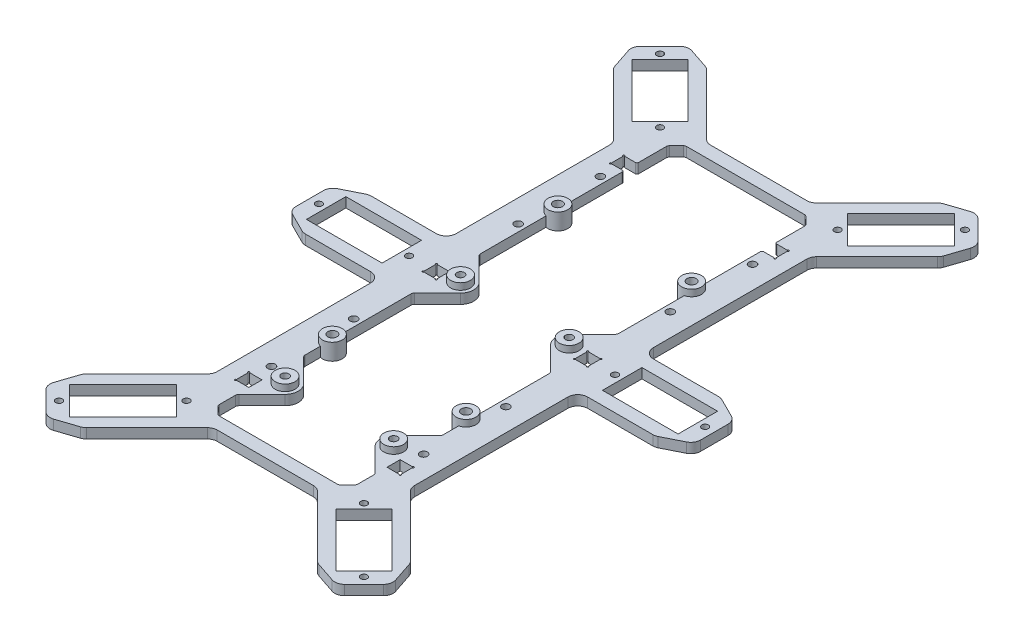
SolidWorks part; units mm, degrees
ref_plane "前视基准面" through (0, 0, 0) normal (0, 0, 1) x (1, 0, 0)
ref_plane "上视基准面" through (0, 0, 0) normal (0, 1, 0) x (1, 0, 0)
ref_plane "右视基准面" through (0, 0, 0) normal (1, 0, 0) x (0, 0, -1)
sketch "草图1" plane through (0, 0, 0) normal (0, 1, 0) x (1, 0, 0)
  line L0 (-30, 65) -> (-20, 75)
  line L1 (-20.5, 38) -> (20.5, 38) construction
  line L2 (-20.5, 38) -> (-20.5, -38) construction
  line L3 (-20.5, -38) -> (20.5, -38) construction
  line L4 (20.5, 38) -> (20.5, -38) construction
  line L5 (-20.5, 38) -> (20.5, -38) construction
  line L6 (-20.5, -38) -> (20.5, 38) construction
  line L7 (-20, 75) -> (20, 75)
  line L8 (-30, 65) -> (-30, -65)
  line L9 (-20, -75) -> (20, -75)
  line L10 (30, 65) -> (30, -65)
  line L11 (-30, 75) -> (30, -75) construction
  line L12 (-30, -75) -> (30, 75) construction
  line L13 (20, 75) -> (30, 65)
  line L14 (30, -65) -> (20, -75)
  line L15 (-30, -65) -> (-20, -75)
  line L16 (-1.6778, 71) -> (18.3431, 71)
  line L17 (18.3431, 71) -> (21, 68.3431)
  line L18 (21, 68.3431) -> (21, -68.3431)
  line L19 (0, 0) -> (21, 0) construction
  line L20 (0, 0) -> (0, 17.6719) construction
  line L21 (18.3431, -71) -> (21, -68.3431)
  line L22 (-1.6778, -71) -> (18.3431, -71)
  line L23 (1.6778, -71) -> (-18.3431, -71)
  line L24 (-18.3431, -71) -> (-21, -68.3431)
  line L25 (-21, 68.3431) -> (-21, -68.3431)
  line L26 (-18.3431, 71) -> (-21, 68.3431)
  line L27 (1.6778, 71) -> (-18.3431, 71)
  point P0 (0, 0)
  point P6 (0, 0)
  dimension "D1" = 41
  dimension "D2" = 76
  dimension "D3" = 60
  dimension "D4" = 150
  dimension "D5" = 9
  dimension "D6" = 4
  dimension "D11" = 4
extrude "凸台-拉伸1" add sketch "草图1" along normal mid plane 3 contours L8 L15 L9 L14 L10 L13 L7 L0 L27 L16 L17 L18 L21 L22 L23 L24 L25 L26
sketch "草图2" plane through (0, 1.5, 0) normal (0, 1, 0) x (1, 0, 0)
  line L0 (0, 0) -> (45, 0) construction
  line L1 (33.5, 6) -> (56.5, 6)
  line L2 (33.5, 6) -> (33.5, -6)
  line L3 (33.5, -6) -> (56.5, -6)
  line L4 (56.5, 6) -> (56.5, -6)
  line L5 (33.5, 6) -> (56.5, -6) construction
  line L6 (33.5, -6) -> (56.5, 6) construction
  line L7 (25, 70) -> (46.3546, 91.3546) construction
  line L8 (28.5, 10) -> (60.5, 10)
  line L9 (28.5, 10) -> (28.5, -10)
  line L10 (28.5, -10) -> (60.5, -10)
  line L11 (61.5, 9) -> (61.5, -9)
  line L12 (28.5, 10) -> (61.5, -10) construction
  line L13 (28.5, -10) -> (61.5, 10) construction
  line L14 (20, 75) -> (30, 65) construction
  line L15 (24.2929, 77.7782) -> (32.7782, 69.2929)
  line L20 (24.2929, 77.7782) -> (40.5563, 94.0416)
  line L21 (32.7782, 69.2929) -> (49.0416, 85.5563)
  line L22 (40.5563, 94.0416) -> (49.0416, 85.5563)
  line L23 (44.799, 89.799) -> (28.5355, 73.5355) construction
  line L33 (54.6985, 85.5563) -> (30, 60.8579)
  line L34 (40.5563, 99.6985) -> (15.8579, 75)
  line L35 (41.9706, 99.6985) -> (54.6985, 86.9706)
  line L36 (20, 75) -> (30, 65)
  line L37 (45, 0) -> (58.7, 0) construction
  line L38 (45, 0) -> (45, 5.0576) construction
  line L39 (32.4246, 85.9099) -> (40.9099, 77.4246) construction
  line L40 (30, 65) -> (30, 60.8579)
  line L42 (20, 75) -> (15.8579, 75)
  arc A0 (60.5, -10) -> (61.5, -9) centre (60.5, -9) ccw
  arc A1 (60.5, 10) -> (61.5, 9) centre (60.5, 9) cw
  circle A4 centre (58.7, 0) radius 1
  circle A5 centre (31.3, 0) radius 1
  circle A6 centre (46.3546, 91.3546) radius 1
  circle A7 centre (26.9799, 71.9799) radius 1
  arc A8 (54.6985, 85.5563) -> (54.6985, 86.9706) centre (53.9914, 86.2635) ccw
  arc A9 (40.5563, 99.6985) -> (41.9706, 99.6985) centre (41.2635, 98.9914) cw
  point P0 (45, 0)
  dimension "D9" = 1
  dimension "D10" = 2
  dimension "D12" = 2
  dimension "D17" = 1
  dimension "D1" = 23
  dimension "D2" = 12
  dimension "D3" = 20
  dimension "D4" = 5
  dimension "D5" = 45
  dimension "D6" = 23
  dimension "D7" = 12
  dimension "D8" = 4
  dimension "D11" = 27.4
  dimension "D13" = 27.4
  dimension "D14" = 5
  dimension "D15" = 4
  dimension "D16" = 5
extrude "凸台-拉伸2" add sketch "草图2" against normal through all
mirror "镜向1" about plane through (0, 0, 0) normal (0, 0, 1) of "凸台-拉伸2"
mirror "镜向2" about plane through (0, 0, 0) normal (1, 0, 0) of "镜向1", "凸台-拉伸2"
sketch "草图3" plane through (0, 1.5, 0) normal (0, 1, 0) x (1, 0, 0)
  line L0 (16.51, 0.8674) -> (21, 0.8674) construction
  line L1 (21, 68.3431) -> (21, -68.3431) construction
  line L2 (21, 11.0142) -> (13.6816, 3.6958)
  line L3 (21, 2.25) -> (21, 54.75) construction
  line L4 (21, -9.2794) -> (13.6816, -1.961)
  line L5 (21, 11.0142) -> (21, -9.2794)
  line L6 (21, -54.75) -> (21, -2.25) construction
  line L9 (5.744, -25.8034) -> (19.0373, -25.8034) construction
  line L10 (19.0373, 0.8674) -> (19.0373, -52.4742) construction
  line L11 (21, -62.621) -> (21, -42.3273)
  line L12 (21, -42.3273) -> (13.6816, -49.6457)
  line L13 (21, -62.621) -> (13.6816, -55.3026)
  line L14 (0, -63) -> (0, -56.7778) construction
  line L15 (-4.17, -63) -> (4.17, -63) construction
  line L16 (-21, 11.0142) -> (-21, -9.2794)
  line L17 (-21, -9.2794) -> (-13.6816, -1.961)
  line L18 (-21, 11.0142) -> (-13.6816, 3.6958)
  line L19 (-21, -62.621) -> (-13.6816, -55.3026)
  line L20 (-21, -62.621) -> (-21, -42.3273)
  line L21 (-21, -42.3273) -> (-13.6816, -49.6457)
  circle A0 centre (16.51, 0.8674) radius 1.15
  circle A1 centre (16.51, -52.4727) radius 1.15
  circle A2 centre (-16.51, -52.4727) radius 1.15
  circle A3 centre (-16.51, 0.8674) radius 1.15
  arc A4 (13.6816, 3.6958) -> (13.6816, -1.961) centre (16.51, 0.8674) ccw
  arc A6 (13.6816, -55.3026) -> (13.6816, -49.6457) centre (16.51, -52.4742) cw
  arc A7 (-13.6816, 3.6958) -> (-13.6816, -1.961) centre (-16.51, 0.8674) cw
  arc A8 (-13.6816, -55.3026) -> (-13.6816, -49.6457) centre (-16.51, -52.4742) ccw
  dimension "D1" = 2.3
  dimension "D2" = 2.3
  dimension "D3" = 2.3
  dimension "D4" = 2.3
  dimension "D5" = 8
  dimension "D6" = 45
extrude "凸台-拉伸3" add sketch "草图3" against normal blind 3
sketch "草图4" plane through (0, 1.5, 0) normal (0, 1, 0) x (1, 0, 0)
  line L0 (0, -71) -> (0, -45.2799) construction
  line L1 (-18.3431, -71) -> (18.3431, -71) construction
  circle A0 centre (16.51, -52.4727) radius 1.15 construction
  circle A1 centre (16.51, 0.8674) radius 1.15 construction
  circle A2 centre (16.51, -52.4727) radius 1.15
  circle A3 centre (16.51, 0.8674) radius 1.15
  circle A4 centre (16.51, -52.4727) radius 3
  circle A5 centre (16.51, 0.8674) radius 3
  circle A6 centre (-16.51, 0.8674) radius 3
  circle A7 centre (-16.51, 0.8674) radius 1.15
  circle A8 centre (-16.51, -52.4727) radius 3
  circle A9 centre (-16.51, -52.4727) radius 1.15
  dimension "D1" = 6
  dimension "D2" = 6
extrude "凸台-拉伸4" add sketch "草图4" along normal blind 2
sketch "草图5" plane through (0, 1.5, 0) normal (0, 1, 0) x (1, 0, 0)
  line L0 (21, 68.3431) -> (21, 11.0142) construction
  line L1 (21, 2) -> (25, 2)
  line L2 (21, 2) -> (21, -2)
  line L3 (21, -2) -> (25, -2)
  line L4 (25, 2) -> (25, -2)
  line L5 (21, 2) -> (25, -2) construction
  line L6 (21, -2) -> (25, 2) construction
  line L7 (0, 0) -> (23, 0) construction
  line L8 (21, -55) -> (25, -55)
  line L9 (21, 59) -> (25, 59)
  line L10 (21, 59) -> (21, 55)
  line L11 (21, 55) -> (25, 55)
  line L12 (25, 59) -> (25, 55)
  line L13 (21, 59) -> (25, 55) construction
  line L14 (21, 55) -> (25, 59) construction
  line L15 (25, -59) -> (25, -55)
  line L16 (21, -59) -> (25, -59)
  line L17 (21, -59) -> (21, -55)
  line L18 (0, 0) -> (0, 27.4251) construction
  line L19 (-21, -59) -> (-21, -55)
  line L20 (-21, -59) -> (-25, -59)
  line L21 (-25, -59) -> (-25, -55)
  line L22 (-21, -55) -> (-25, -55)
  line L23 (-21, -2) -> (-25, -2)
  line L24 (-25, 2) -> (-25, -2)
  line L25 (-21, 2) -> (-25, 2)
  line L26 (-21, 2) -> (-21, -2)
  line L27 (-21, 55) -> (-25, 55)
  line L28 (-25, 59) -> (-25, 55)
  line L29 (-21, 59) -> (-25, 59)
  line L30 (-21, 59) -> (-21, 55)
  point P0 (23, 0)
  point P10 (23, 57)
  dimension "D1" = 4
  dimension "D2" = 4
  dimension "D3" = 4
  dimension "D4" = 4
  dimension "D5" = 110
extrude "切除-拉伸1" cut sketch "草图5" against normal blind 3
sketch "草图6" plane through (0, 1.5, 0) normal (0, 1, 0) x (1, 0, 0)
  line L0 (0, 0) -> (5.4753, 0) construction
  line L1 (0, 0) -> (0, 5.5062) construction
  circle A0 centre (25, 59) radius 0.25
  circle A1 centre (25, 55) radius 0.25
  circle A2 centre (25, 2) radius 0.25
  circle A3 centre (21, 2) radius 0.25
  circle A4 centre (25, -55) radius 0.25
  circle A5 centre (25, -59) radius 0.25
  circle A6 centre (21, -2) radius 0.25
  circle A7 centre (25, -2) radius 0.25
  circle A8 centre (-25, -2) radius 0.25
  circle A9 centre (-21, -2) radius 0.25
  circle A10 centre (-25, -59) radius 0.25
  circle A11 centre (-25, -55) radius 0.25
  circle A12 centre (-21, 2) radius 0.25
  circle A13 centre (-25, 2) radius 0.25
  circle A14 centre (-25, 55) radius 0.25
  circle A15 centre (-25, 59) radius 0.25
  dimension "D1" = 0.5
  dimension "D2" = 0.5
  dimension "D3" = 0.5
  dimension "D4" = 0.5
extrude "切除-拉伸2" cut sketch "草图6" against normal blind 3
fillet "圆角1" radius 0.5 4 edges at (-21, 0, -55) (-21, 0, -59) (21, 0, -59) (21, 0, -55)
fillet "圆角2" radius 1 16 edges at (-18.3431, 0, -71) (-21, 0, -68.3431) (18.3431, 0, -71) (21, 0, -68.3431) (21, 0, -11.0142) (-21, 0, -11.0142) (-21, 0, 9.2794) (21, 0, 9.2794) (21, 0, 42.3273) (-21, 0, 42.3273) (-21, 0, 62.621) (-21, 0, 68.3431) (-18.3431, 0, 71) (21, 0, 62.621) (21, 0, 68.3431) (18.3431, 0, 71)
fillet "圆角3" radius 3 6 edges at (30, 0, -10) (-30, 0, -10) (-30, 0, -60.8579) (-15.8579, 0, -75) (15.8579, 0, -75) (30, 0, -60.8579)
fillet "圆角4" radius 3 6 edges at (-30, 0, 10) (30, 0, 10) (30, 0, 60.8579) (-30, 0, 60.8579) (-15.8579, 0, 75) (15.8579, 0, 75)
sketch "草图7" plane through (0, 1.5, 0) normal (0, 1, 0) x (1, 0, 0)
  line L0 (23.125, 59) -> (23.125, 50) construction
  line L1 (24.75, 59) -> (21.5, 59) construction
  line L2 (23.125, 50) -> (23.125, 25) construction
  line L3 (0, 0) -> (10.174, 0) construction
  line L4 (0, 0) -> (0, 32.9356) construction
  circle A0 centre (23.125, 50) radius 1.15
  circle A1 centre (23.125, 25) radius 1.15
  circle A2 centre (23.125, -50) radius 1.15
  circle A3 centre (23.125, -25) radius 1.15
  circle A4 centre (-23.125, 50) radius 1.15
  circle A5 centre (-23.125, 25) radius 1.15
  circle A6 centre (-23.125, -25) radius 1.15
  circle A7 centre (-23.125, -50) radius 1.15
  dimension "D1" = 2.3
  dimension "D2" = 2.3
  dimension "D3" = 25
  dimension "D4" = 25
extrude "切除-拉伸3" cut sketch "草图7" against normal through all
sketch "草图8" plane through (0, 1.5, 0) normal (0, 1, 0) x (1, 0, 0)
  line L0 (53.5, 10) -> (61.5, 6)
  line L1 (60.5, 10) -> (33, 10) construction
  line L2 (61.5, -9) -> (61.5, 9) construction
  line L3 (61.5, -9) -> (61.5, -6)
  line L4 (60.5, 10) -> (53.5, 10)
  line L5 (0, 0) -> (10.8263, 0) construction
  line L6 (53.5, -10) -> (61.5, -6)
  line L7 (33, -10) -> (60.5, -10) construction
  line L8 (53.5, -10) -> (60.5, -10)
  line L9 (61.5, 6) -> (61.5, 9)
  line L10 (52.5772, -89.0919) -> (49.7487, -80.6066)
  line L11 (54.6985, -86.9706) -> (41.9706, -99.6985) construction
  line L12 (30.8787, -61.7365) -> (54.6985, -85.5563) construction
  line L13 (26.9799, -71.9799) -> (34.1605, -79.1605) construction
  line L14 (32.7782, -69.2929) -> (49.0416, -85.5563) construction
  line L15 (44.0919, -97.5772) -> (35.6066, -94.7487)
  line L16 (40.5563, -99.6985) -> (16.7365, -75.8787) construction
  line L17 (40.5563, -99.6985) -> (35.6066, -94.7487)
  line L18 (49.7487, -80.6066) -> (54.6985, -85.5563)
  line L19 (54.6985, -86.9706) -> (52.5772, -89.0919)
  line L20 (44.0919, -97.5772) -> (41.9706, -99.6985)
  line L21 (40.5563, 99.6985) -> (35.6066, 94.7487)
  line L22 (44.0919, 97.5772) -> (35.6066, 94.7487)
  line L23 (44.0919, 97.5772) -> (41.9706, 99.6985)
  line L24 (49.7487, 80.6066) -> (54.6985, 85.5563)
  line L25 (52.5772, 89.0919) -> (49.7487, 80.6066)
  line L26 (54.6985, 86.9706) -> (52.5772, 89.0919)
  line L27 (0, 0) -> (0, 12.3518) construction
  line L28 (-54.6985, 86.9706) -> (-52.5772, 89.0919)
  line L29 (-52.5772, 89.0919) -> (-49.7487, 80.6066)
  line L30 (-49.7487, 80.6066) -> (-54.6985, 85.5563)
  line L31 (-44.0919, 97.5772) -> (-41.9706, 99.6985)
  line L32 (-44.0919, 97.5772) -> (-35.6066, 94.7487)
  line L33 (-40.5563, 99.6985) -> (-35.6066, 94.7487)
  line L34 (-44.0919, -97.5772) -> (-41.9706, -99.6985)
  line L35 (-54.6985, -86.9706) -> (-52.5772, -89.0919)
  line L36 (-49.7487, -80.6066) -> (-54.6985, -85.5563)
  line L37 (-40.5563, -99.6985) -> (-35.6066, -94.7487)
  line L38 (-44.0919, -97.5772) -> (-35.6066, -94.7487)
  line L39 (-52.5772, -89.0919) -> (-49.7487, -80.6066)
  line L40 (-61.5, 6) -> (-61.5, 9)
  line L41 (-53.5, -10) -> (-60.5, -10)
  line L42 (-53.5, -10) -> (-61.5, -6)
  line L43 (-60.5, 10) -> (-53.5, 10)
  line L44 (-61.5, -9) -> (-61.5, -6)
  line L45 (-53.5, 10) -> (-61.5, 6)
  arc A0 (61.5, 9) -> (60.5, 10) centre (60.5, 9) ccw construction
  arc A1 (61.5, 9) -> (60.5, 10) centre (60.5, 9) ccw
  arc A2 (60.5, -10) -> (61.5, -9) centre (60.5, -9) ccw construction
  arc A3 (60.5, -10) -> (61.5, -9) centre (60.5, -9) ccw
  arc A4 (40.5563, -99.6985) -> (41.9706, -99.6985) centre (41.2635, -98.9914) ccw construction
  arc A5 (54.6985, -86.9706) -> (54.6985, -85.5563) centre (53.9914, -86.2635) ccw construction
  arc A6 (40.5563, -99.6985) -> (41.9706, -99.6985) centre (41.2635, -98.9914) ccw
  arc A7 (54.6985, -86.9706) -> (54.6985, -85.5563) centre (53.9914, -86.2635) ccw
  arc A8 (40.5563, 99.6985) -> (41.9706, 99.6985) centre (41.2635, 98.9914) cw
  arc A9 (54.6985, 86.9706) -> (54.6985, 85.5563) centre (53.9914, 86.2635) cw
  arc A10 (-54.6985, 86.9706) -> (-54.6985, 85.5563) centre (-53.9914, 86.2635) ccw
  arc A11 (-40.5563, 99.6985) -> (-41.9706, 99.6985) centre (-41.2635, 98.9914) ccw
  arc A12 (-54.6985, -86.9706) -> (-54.6985, -85.5563) centre (-53.9914, -86.2635) cw
  arc A13 (-40.5563, -99.6985) -> (-41.9706, -99.6985) centre (-41.2635, -98.9914) cw
  arc A14 (-60.5, -10) -> (-61.5, -9) centre (-60.5, -9) cw
  arc A15 (-61.5, 9) -> (-60.5, 10) centre (-60.5, 9) cw
  dimension "D1" = 4
  dimension "D2" = 8
  dimension "D3" = 4
  dimension "D4" = 8
extrude "切除-拉伸4" cut sketch "草图8" against normal up to next
fillet "圆角5" radius 3 12 edges at (35.6066, 0, 94.7487) (44.0919, 0, 97.5772) (49.7487, 0, 80.6066) (52.5772, 0, 89.0919) (49.7487, 0, -80.6066) (35.6066, 0, -94.7487) (44.0919, 0, -97.5772) (52.5772, 0, -89.0919) (53.5, 0, -10) (61.5, 0, -6) (53.5, 0, 10) (61.5, 0, 6)
fillet "圆角6" radius 3 12 edges at (-35.6066, 0, -94.7487) (-44.0919, 0, -97.5772) (-52.5772, 0, -89.0919) (-49.7487, 0, -80.6066) (-53.5, 0, 10) (-61.5, 0, 6) (-53.5, 0, -10) (-61.5, 0, -6) (-49.7487, 0, 80.6066) (-52.5772, 0, 89.0919) (-44.0919, 0, 97.5772) (-35.6066, 0, 94.7487)
sketch "草图9" plane through (0, 1.5, 0) normal (0, 1, 0) x (1, 0, 0)
  line L1 (-20.32, 34.29) -> (20.32, 34.29) construction
  line L2 (-20.32, 34.29) -> (-20.32, -34.29) construction
  line L3 (-20.32, -34.29) -> (20.32, -34.29) construction
  line L4 (20.32, 34.29) -> (20.32, -34.29) construction
  line L5 (-20.32, 34.29) -> (20.32, -34.29) construction
  line L6 (-20.32, -34.29) -> (20.32, 34.29) construction
  circle A1 centre (-20.32, -34.29) radius 3
  circle A2 centre (20.32, -34.29) radius 3
  circle A3 centre (20.32, 34.29) radius 3
  circle A4 centre (-20.32, 34.29) radius 3
  point P0 (0, 0)
  dimension "D4" = 6
  dimension "D5" = 6
  dimension "D6" = 6
  dimension "D7" = 6
  dimension "D1" = 40.64
  dimension "D2" = 68.58
extrude "凸台-拉伸5" add sketch "草图9" along normal blind 2 and the other way blind 3
sketch "草图10" plane through (0, 3.5, 0) normal (0, 1, 0) x (1, 0, 0)
  circle A0 centre (20.32, 34.29) radius 1.4
  circle A1 centre (-20.32, 34.29) radius 1.4
  circle A2 centre (20.32, -34.29) radius 1.4
  circle A3 centre (20.32, -34.29) radius 3 construction
  circle A4 centre (-20.32, -34.29) radius 1.4
  dimension "D1" = 2.8
  dimension "D2" = 2.8
  dimension "D3" = 2.8
  dimension "D4" = 2.8
extrude "切除-拉伸5" cut sketch "草图10" against normal through all
